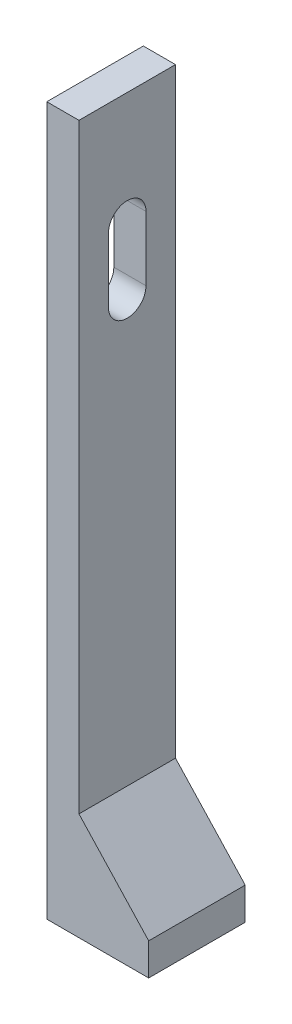
SolidWorks part; units mm, degrees
material "ПВХ Жесткий"
ref_plane "Спереди" through (0, 0, 0) normal (0, 0, 1) x (1, 0, 0)
ref_plane "Сверху" through (0, 0, 0) normal (0, 1, 0) x (1, 0, 0)
ref_plane "Справа" through (0, 0, 0) normal (1, 0, 0) x (0, 0, -1)
sketch "Эскиз1" plane through (0, 0, 0) normal (0, 0, 1) x (1, 0, 0)
  line L0 (0, 0) -> (9.5, 0)
  line L1 (9.5, 0) -> (9.5, 3)
  line L2 (9.5, 3) -> (3, 3)
  line L3 (3, 3) -> (3, 66)
  line L4 (3, 66) -> (0, 66)
  line L5 (0, 66) -> (0, 0)
  dimension "D1" = 3
  dimension "D2" = 66
  dimension "D3" = 9.5
extrude "Бобышка-Вытянуть1" add sketch "Эскиз1" along normal blind 9
sketch "Эскиз2" plane through (3, 0, 0) normal (1, 0, 0) x (0, 0, -1)
  line L0 (-4.5, 66) -> (-4.5, 3) construction
  line L1 (-9, 66) -> (0, 66) construction
  line L2 (-9, 3) -> (0, 3) construction
ref_plane "Плоскость1" through (0, 0, 4.5) normal (0, 0, 1) x (0, -1, 0)
sketch "Эскиз3" plane through (0, 0, 0) normal (-1, 0, 0) x (0, 0, 1)
  line L0 (9, 66) -> (0, 66) construction
  line L1 (4.5, 66) -> (4.5, 3) construction
  line L2 (4.5, 66) -> (4.5, 3) construction
  circle A1 centre (4.5, 52.52) radius 1.75
  dimension "D1" = 13.48
  dimension "D2" = 3.5
sketch "Эскиз4" plane through (0, 0, 0) normal (-1, 0, 0) x (0, 0, 1)
  line L0 (4.5, 55.52) -> (4.5, 49.52) construction
  line L1 (6.25, 55.52) -> (6.25, 49.52)
  line L2 (2.75, 55.52) -> (2.75, 49.52)
  line L3 (4.5, 66) -> (4.5, 43.3234) construction
  line L4 (9, 66) -> (0, 66) construction
  circle A0 centre (4.5, 52.52) radius 1.75 construction
  circle A1 centre (4.5, 52.52) radius 1.75 construction
  arc A2 (6.25, 55.52) -> (2.75, 55.52) centre (4.5, 55.52) ccw
  arc A3 (2.75, 49.52) -> (6.25, 49.52) centre (4.5, 49.52) ccw
  point P5 (4.5, 52.52)
  dimension "D1" = 6
extrude "Вырез-Вытянуть2" cut sketch "Эскиз4" against normal through all
sketch "Эскиз5" plane through (0, 0, 9) normal (0, 0, 1) x (1, 0, 0)
  line L0 (3, 3) -> (3, 66) construction
  line L1 (9.5, 3) -> (3, 3) construction
  line L2 (3, 3) -> (3, 10)
  line L3 (9.5, 3) -> (3, 3)
  line L4 (9.5, 3) -> (3, 10)
  dimension "D1" = 7
extrude "Бобышка-Вытянуть2" add sketch "Эскиз5" against normal through all
